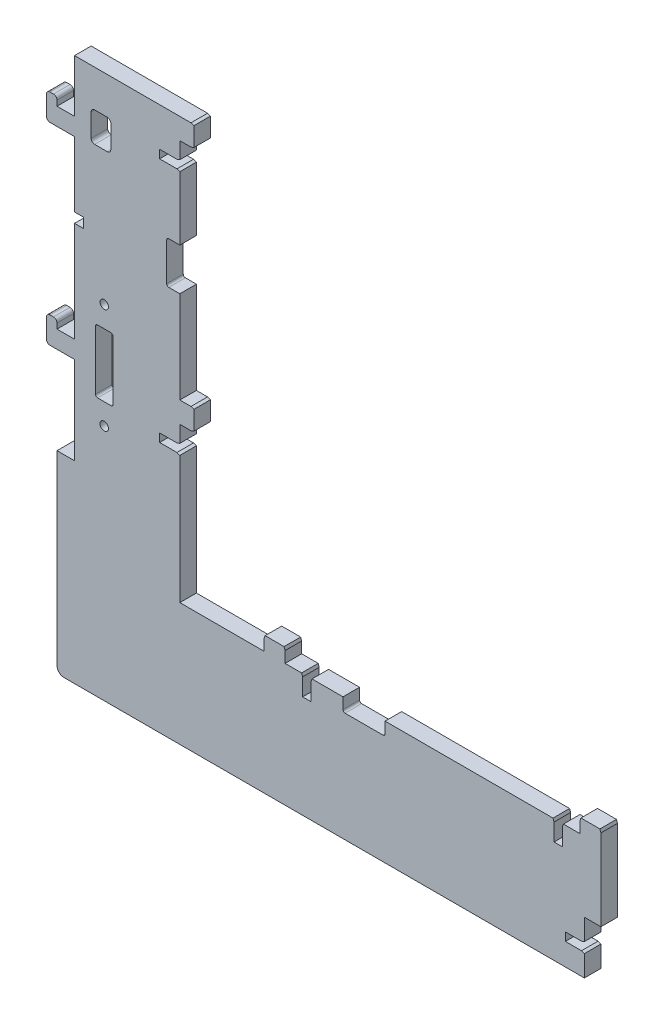
SolidWorks part; units mm, degrees
ref_plane "Front Plane" through (0, 0, 0) normal (0, 0, 1) x (1, 0, 0)
ref_plane "Top Plane" through (0, 0, 0) normal (0, 1, 0) x (1, 0, 0)
ref_plane "Right Plane" through (0, 0, 0) normal (1, 0, 0) x (0, 0, -1)
sketch "Sketch1" plane through (0, 0, 0) normal (0, 0, 1) x (1, 0, 0)
  line L0 (0, 0) -> (190.5, 0)
  line L1 (190.5, 0) -> (190.5, 44.45)
  line L2 (190.5, 44.45) -> (38.1, 44.45)
  line L3 (38.1, 44.45) -> (38.1, 196.85)
  line L4 (38.1, 196.85) -> (0, 196.85)
  line L5 (0, 196.85) -> (0, 0)
  dimension "D1" = 152.4
  dimension "D2" = 44.45
  dimension "D3" = 38.1
  dimension "D4" = 152.4
extrude "Boss-Extrude1" add sketch "Sketch1" along normal blind 6
sketch "Sketch2" plane through (0, 0, 6) normal (0, 0, 1) x (1, 0, 0)
  line L0 (0, 177.8) -> (-6.35, 177.8)
  line L1 (0, 0) -> (-6.35, 0)
  line L2 (0, 0) -> (0, 69.85)
  line L3 (0, 69.85) -> (-6.35, 69.85)
  line L4 (-6.35, 0) -> (-6.35, 69.85)
  line L5 (0, 196.85) -> (0, 0) construction
  line L6 (-6.35, 177.8) -> (-6.35, 180.975)
  line L7 (-6.35, 180.975) -> (-10.16, 180.975)
  line L8 (-10.16, 180.975) -> (-10.16, 171.45)
  line L9 (-10.16, 171.45) -> (0, 171.45)
  line L10 (0, 107.95) -> (-6.35, 107.95)
  line L11 (-6.35, 107.95) -> (-6.35, 111.125)
  line L12 (-6.35, 111.125) -> (-10.16, 111.125)
  line L13 (-10.16, 111.125) -> (-10.16, 101.6)
  line L14 (-10.16, 101.6) -> (0, 101.6)
  line L15 (0, 107.95) -> (0, 101.6)
  line L16 (0, 177.8) -> (0, 171.45)
  line L17 (38.1, 196.85) -> (0, 196.85) construction
  line L18 (190.5, 44.45) -> (38.1, 44.45) construction
  line L19 (68.58, 44.45) -> (76.2, 44.45)
  line L20 (68.58, 44.45) -> (68.58, 49.53)
  line L21 (68.58, 49.53) -> (76.2, 49.53)
  line L22 (76.2, 44.45) -> (76.2, 49.53)
  line L23 (38.1, 44.45) -> (38.1, 196.85) construction
  line L24 (190.5, 44.45) -> (182.88, 44.45)
  line L25 (190.5, 44.45) -> (190.5, 49.53)
  line L26 (190.5, 49.53) -> (182.88, 49.53)
  line L27 (182.88, 44.45) -> (182.88, 49.53)
  line L28 (38.1, 196.85) -> (43.18, 196.85)
  line L29 (38.1, 196.85) -> (38.1, 189.23)
  line L30 (38.1, 189.23) -> (43.18, 189.23)
  line L31 (43.18, 196.85) -> (43.18, 189.23)
  line L32 (38.1, 107.95) -> (43.18, 107.95)
  line L33 (38.1, 107.95) -> (38.1, 100.33)
  line L34 (38.1, 100.33) -> (43.18, 100.33)
  line L35 (43.18, 107.95) -> (43.18, 100.33)
  line L36 (190.5, 0) -> (190.5, 44.45) construction
  dimension "D1" = 6.35
  dimension "D2" = 127
  dimension "D3" = 3.175
  dimension "D4" = 6.35
  dimension "D5" = 3.81
  dimension "D6" = 19.05
  dimension "D7" = 88.9
  dimension "D8" = 7.62
  dimension "D9" = 5.08
  dimension "D10" = 114.3
  dimension "D11" = 88.9
extrude "Boss-Extrude2" add sketch "Sketch2" against normal up to surface (6 mm away) up to face at (76.2, 80.4333, 0)
fillet "Fillet1" radius 1.27 6 edges at (-6.35, 111.125, 3) (-6.35, 180.975, 3) (-10.16, 101.6, 3) (-10.16, 111.125, 3) (-10.16, 171.45, 3) (-10.16, 180.975, 3)
sketch "Sketch3" plane through (0, 0, 6) normal (0, 0, 1) x (1, 0, 0)
  line L1 (190.5, 0) -> (184.5, 0)
  line L2 (190.5, 0) -> (190.5, 19.05)
  line L3 (190.5, 19.05) -> (184.5, 19.05)
  line L4 (184.5, 0) -> (184.5, 19.05)
  dimension "D1" = 6
  dimension "D2" = 19.05
extrude "Cut-Extrude1" cut sketch "Sketch3" against normal through all
fillet "Fillet2" radius 2.54 1 edges at (-6.35, 0, 3)
sketch "Sketch4" plane through (0, 0, 6) normal (0, 0, 1) x (1, 0, 0)
  line L0 (14.6868, 183.4515) -> (7.5748, 183.4515) construction
  line L1 (13.112, 183.4515) -> (6, 183.4515)
  line L2 (13.112, 183.4515) -> (13.112, 172.6565)
  line L3 (13.112, 172.6565) -> (6, 172.6565)
  line L4 (6, 183.4515) -> (6, 172.6565)
  line L5 (6, 190.5) -> (6, 90.424) construction
  line L6 (14.6868, 172.6565) -> (7.5748, 172.6565) construction
  line L7 (14.6868, 183.4515) -> (14.6868, 172.6565) construction
  line L8 (0, 171.45) -> (0, 107.95) construction
  line L9 (0, 147.828) -> (3.175, 147.828)
  line L10 (0, 147.828) -> (0, 144.272)
  line L11 (0, 144.272) -> (3.175, 144.272)
  line L12 (3.175, 147.828) -> (3.175, 144.272)
  line L14 (0, 146.05) -> (3.175, 146.05) construction
  line L15 (43.18, 196.85) -> (0, 196.85) construction
  dimension "D1" = 1.5748
  dimension "D2" = 3.556
  dimension "D3" = 3.175
  dimension "D4" = 50.8
extrude "Cut-Extrude2" cut sketch "Sketch4" against normal through all
fillet "Fillet3" radius 1.27 4 edges at (6, 183.4515, 3) (13.112, 183.4515, 3) (13.112, 172.6565, 3) (6, 172.6565, 3)
sketch "Sketch5" plane through (0, 0, 6) normal (0, 0, 1) x (1, 0, 0)
  line L0 (13.9192, 105.156) -> (14.6812, 105.156) construction
  line L1 (7.5692, 116.586) -> (13.9192, 116.586)
  line L2 (7.5692, 116.586) -> (7.5692, 93.726)
  line L3 (7.5692, 93.726) -> (13.9192, 93.726)
  line L4 (13.9192, 116.586) -> (13.9192, 93.726)
  line L5 (10.7442, 116.586) -> (10.7442, 124.206) construction
  line L6 (10.7442, 93.726) -> (10.7442, 86.106) construction
  line L7 (43.18, 196.85) -> (0, 196.85) construction
  line L8 (0, 101.6) -> (0, 69.85) construction
  circle A0 centre (10.7442, 124.206) radius 1.524
  circle A1 centre (10.7442, 86.106) radius 1.524
  dimension "D3" = 3.048
  dimension "D1" = 6.35
  dimension "D2" = 22.86
  dimension "D4" = 80.264
  dimension "D5" = 7.5692
  dimension "D6" = 38.1
extrude "Cut-Extrude3" cut sketch "Sketch5" against normal through all
sketch "Sketch6" plane through (0, 0, 6) normal (0, 0, 1) x (1, 0, 0)
  line L1 (38.1, 182.88) -> (30.7848, 182.88)
  line L2 (38.1, 182.88) -> (38.1, 179.8828)
  line L3 (38.1, 179.8828) -> (30.7848, 179.8828)
  line L4 (30.7848, 182.88) -> (30.7848, 179.8828)
  line L6 (38.1, 93.98) -> (30.7848, 93.98)
  line L7 (38.1, 93.98) -> (38.1, 90.9828)
  line L8 (38.1, 90.9828) -> (30.7848, 90.9828)
  line L9 (30.7848, 93.98) -> (30.7848, 90.9828)
  line L11 (82.55, 44.45) -> (85.5472, 44.45)
  line L12 (82.55, 44.45) -> (82.55, 37.1348)
  line L13 (82.55, 37.1348) -> (85.5472, 37.1348)
  line L14 (85.5472, 44.45) -> (85.5472, 37.1348)
  line L16 (173.5328, 44.45) -> (176.53, 44.45)
  line L17 (173.5328, 44.45) -> (173.5328, 37.1348)
  line L18 (173.5328, 37.1348) -> (176.53, 37.1348)
  line L19 (176.53, 44.45) -> (176.53, 37.1348)
  line L20 (184.5, 19.05) -> (184.5, 0) construction
  line L21 (184.5, 11.0236) -> (177.642, 11.0236)
  line L22 (184.5, 11.0236) -> (184.5, 8.0264)
  line L23 (184.5, 8.0264) -> (177.642, 8.0264)
  line L24 (177.642, 11.0236) -> (177.642, 8.0264)
  line L25 (177.642, 9.525) -> (184.5, 9.525) construction
  line L26 (175.0314, 37.1348) -> (175.0314, 44.45) construction
  line L27 (84.0486, 37.1348) -> (84.0486, 44.45) construction
  line L28 (30.7848, 92.4814) -> (38.1, 92.4814) construction
  line L29 (30.7848, 181.3814) -> (38.1, 181.3814) construction
  line L30 (38.1, 107.95) -> (38.1, 189.23) construction
  line L31 (38.1, 156.4945) -> (33.3375, 156.4945)
  line L32 (38.1, 156.4945) -> (38.1, 141.2545)
  line L33 (38.1, 141.2545) -> (33.3375, 141.2545)
  line L34 (33.3375, 156.4945) -> (33.3375, 141.2545)
  line L35 (182.88, 44.45) -> (76.2, 44.45) construction
  line L36 (97.1398, 44.45) -> (112.3798, 44.45)
  line L37 (97.1398, 44.45) -> (97.1398, 39.6875)
  line L38 (97.1398, 39.6875) -> (112.3798, 39.6875)
  line L39 (112.3798, 44.45) -> (112.3798, 39.6875)
  line L40 (190.5, 19.05) -> (190.5, 49.53) construction
  line L41 (43.18, 196.85) -> (0, 196.85) construction
  line L42 (38.1, 44.45) -> (38.1, 100.33) construction
  line L43 (38.1, 189.23) -> (43.18, 189.23) construction
  line L44 (38.1, 100.33) -> (43.18, 100.33) construction
  line L45 (76.2, 44.45) -> (76.2, 49.53) construction
  line L46 (182.88, 49.53) -> (182.88, 44.45) construction
  point P52 (33.3375, 148.8745)
  point P53 (104.7598, 39.6875)
  dimension "D1" = 7.3152
  dimension "D2" = 6.858
  dimension "D3" = 2.9972
  dimension "D4" = 85.7402
  dimension "D5" = 47.9755
  dimension "D6" = 15.24
  dimension "D7" = 4.7625
  dimension "D8" = 6.35
  dimension "D9" = 6.35
  dimension "D10" = 6.35
  dimension "D11" = 6.35
extrude "Cut-Extrude4" cut sketch "Sketch6" against normal through all
fillet "Fillet4" radius 0.762 8 edges at (13.9192, 116.586, 3) (7.5692, 116.586, 3) (13.9192, 93.726, 3) (7.5692, 93.726, 3) (112.3798, 39.6875, 3) (97.1398, 39.6875, 3) (33.3375, 141.2545, 3) (33.3375, 156.4945, 3)
chamfer "Chamfer1" distance 0.381 angle 70 10 edges at (82.55, 44.45, 3) (173.5328, 44.45, 3) (176.53, 44.45, 3) (85.5472, 44.45, 3) (38.1, 90.9828, 3) (38.1, 93.98, 3) (38.1, 182.88, 3) (38.1, 179.8828, 3) (184.5, 8.0264, 3) (184.5, 11.0236, 3)
chamfer "Chamfer2" distance 0.381 angle 70 8 edges at (182.88, 49.53, 3) (190.5, 49.53, 3) (76.2, 49.53, 3) (68.58, 49.53, 3) (43.18, 107.95, 3) (43.18, 100.33, 3) (43.18, 189.23, 3) (43.18, 196.85, 3)
